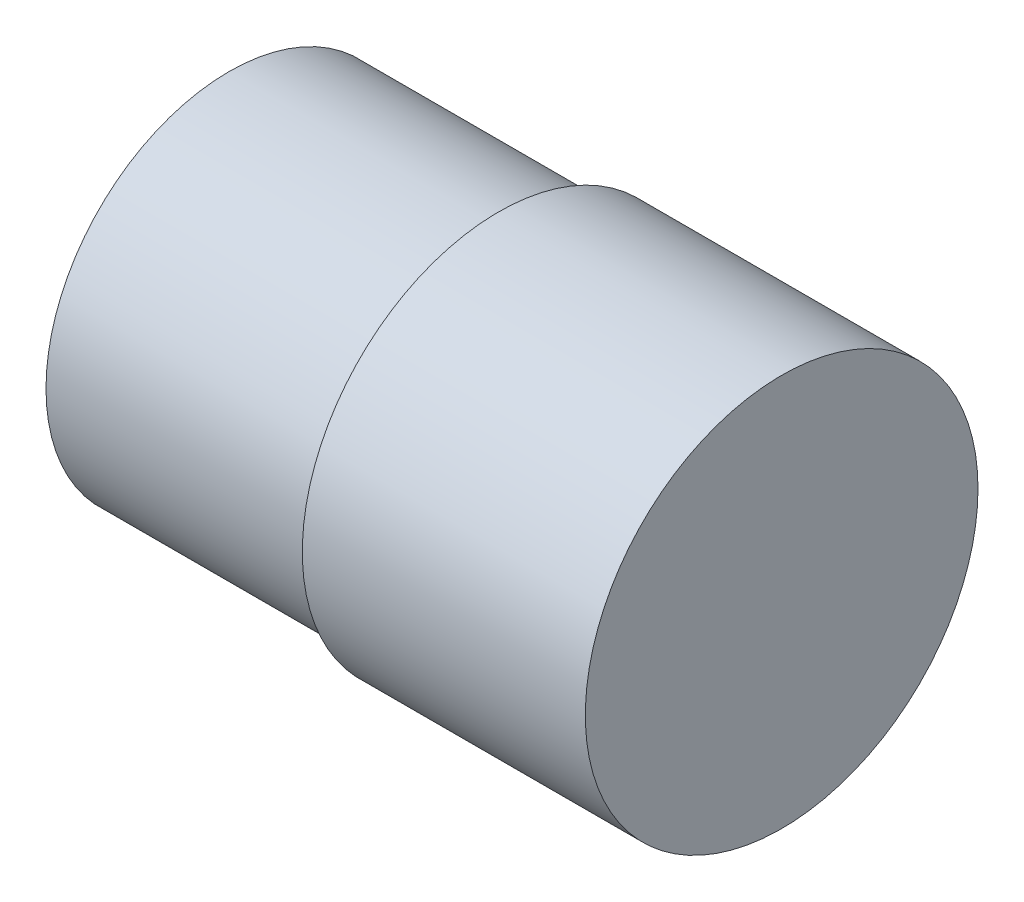
SolidWorks part; units mm, degrees
ref_plane "Front Plane" through (0, 0, 0) normal (0, 0, 1) x (1, 0, 0)
ref_plane "Top Plane" through (0, 0, 0) normal (0, 1, 0) x (1, 0, 0)
ref_plane "Right Plane" through (0, 0, 0) normal (1, 0, 0) x (0, 0, -1)
sketch "Sketch1" plane through (0, 0, 0) normal (1, 0, 0) x (0, 0, -1)
  circle A0 centre (0, 0) radius 18.5
  dimension "D1" = 37
extrude "Boss-Extrude1" add sketch "Sketch1" along normal blind 26.67
sketch "Sketch2" plane through (0, 0, 0) normal (-1, 0, 0) x (0, 0, 1)
  circle A0 centre (0, 0) radius 17.25
  dimension "D1" = 34.5
extrude "Boss-Extrude2" add sketch "Sketch2" along normal blind 25.4
